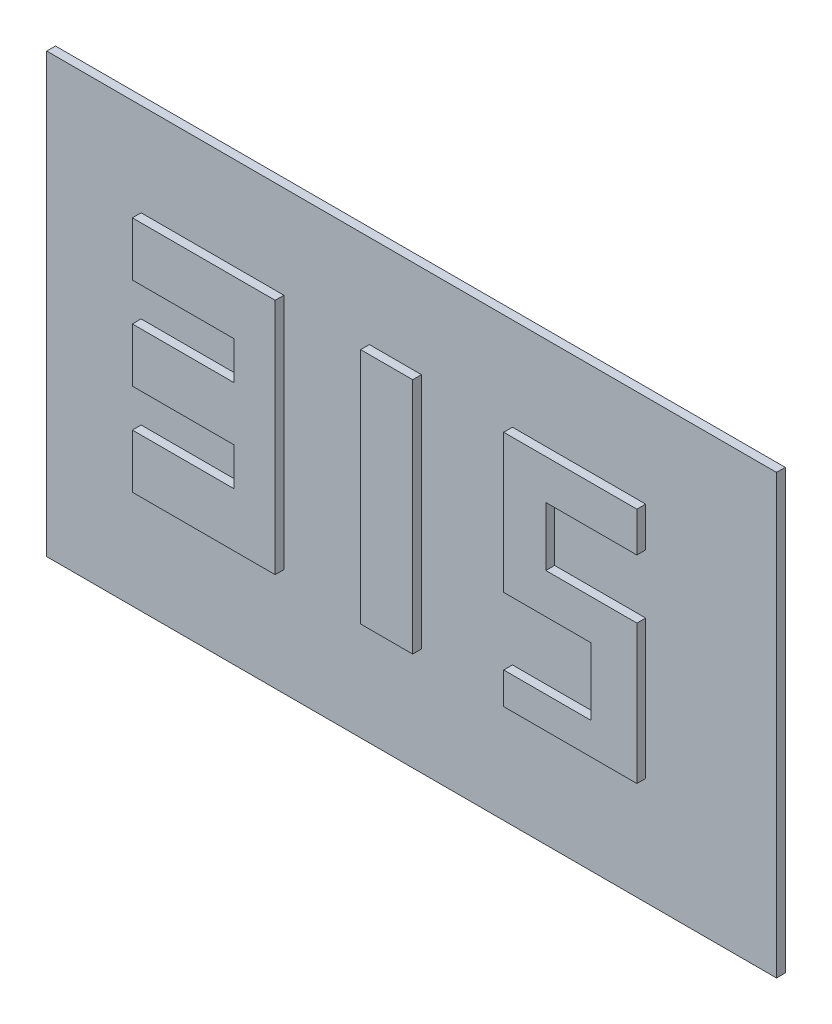
SolidWorks part; units mm, degrees
ref_plane "前视基准面" through (0, 0, 0) normal (0, 0, 1) x (1, 0, 0)
ref_plane "上视基准面" through (0, 0, 0) normal (0, 1, 0) x (1, 0, 0)
ref_plane "右视基准面" through (0, 0, 0) normal (1, 0, 0) x (0, 0, -1)
other "Configuration Table"
sketch "草图1" plane through (0, 0, 0) normal (0, 0, 1) x (1, 0, 0)
  line L1 (0, 0) -> (115.5149, 0)
  line L2 (0, 0) -> (0, 71.0547)
  line L3 (0, 71.0547) -> (115.5149, 71.0547)
  line L4 (115.5149, 0) -> (115.5149, 71.0547)
extrude "凸台-拉伸1" add sketch "草图1" along normal blind 3 contours L2 L1 L4 L3
sketch "草图2" plane through (0, 0, 3) normal (0, 0, 1) x (1, 0, 0)
  line L1 (14.937, 55.9833) -> (37.54, 55.9833)
  line L2 (14.937, 55.9833) -> (14.937, 47.2443)
  line L3 (14.937, 47.2443) -> (31.006, 47.2443)
  line L6 (37.54, 55.9833) -> (37.54, 17.4236)
  line L8 (31.006, 47.2443) -> (31.006, 41.073)
  line L9 (31.006, 41.073) -> (14.937, 41.073)
  line L11 (31.006, 32.334) -> (14.937, 32.334)
  line L12 (14.937, 41.073) -> (14.937, 32.334)
  line L15 (31.006, 26.1627) -> (14.937, 26.1627)
  line L16 (14.937, 17.4236) -> (14.937, 26.1627)
  line L20 (31.006, 32.334) -> (31.006, 26.1627)
  line L21 (14.937, 17.4236) -> (37.54, 17.4236)
  line L22 (73.7197, 17.4236) -> (94.8009, 17.4236)
  line L23 (51.0703, 55.9833) -> (59.3119, 55.9833)
  line L24 (51.0703, 55.9833) -> (51.0703, 17.4236)
  line L25 (51.0703, 17.4236) -> (59.3119, 17.4236)
  line L26 (59.3119, 55.9833) -> (59.3119, 17.4236)
  line L27 (73.7197, 55.9833) -> (94.8009, 55.9833)
  line L29 (80.3924, 49.5399) -> (94.8009, 49.5399)
  line L30 (94.8009, 55.9833) -> (94.8009, 49.5399)
  line L34 (80.3924, 49.5399) -> (80.3924, 39.9737)
  line L35 (80.3924, 39.9737) -> (94.8009, 39.9737)
  line L37 (73.7197, 33.4781) -> (87.5136, 33.4781)
  line L40 (94.8009, 39.9737) -> (94.8009, 17.4236)
  line L42 (87.5136, 33.4781) -> (87.5136, 22.5754)
  line L45 (87.5136, 22.5754) -> (73.7197, 22.5754)
  line L46 (73.7197, 17.4236) -> (73.7197, 22.5754)
  line L47 (73.7197, 33.4781) -> (73.7197, 55.9833)
  point P21 (0, 0)
extrude "凸台-拉伸2" add sketch "草图2" along normal blind 3
scale "缩放比例1" scale about centroid uniform scaling no x scale factor 2.164315 y scale factor 2.111189 z scale factor 1
